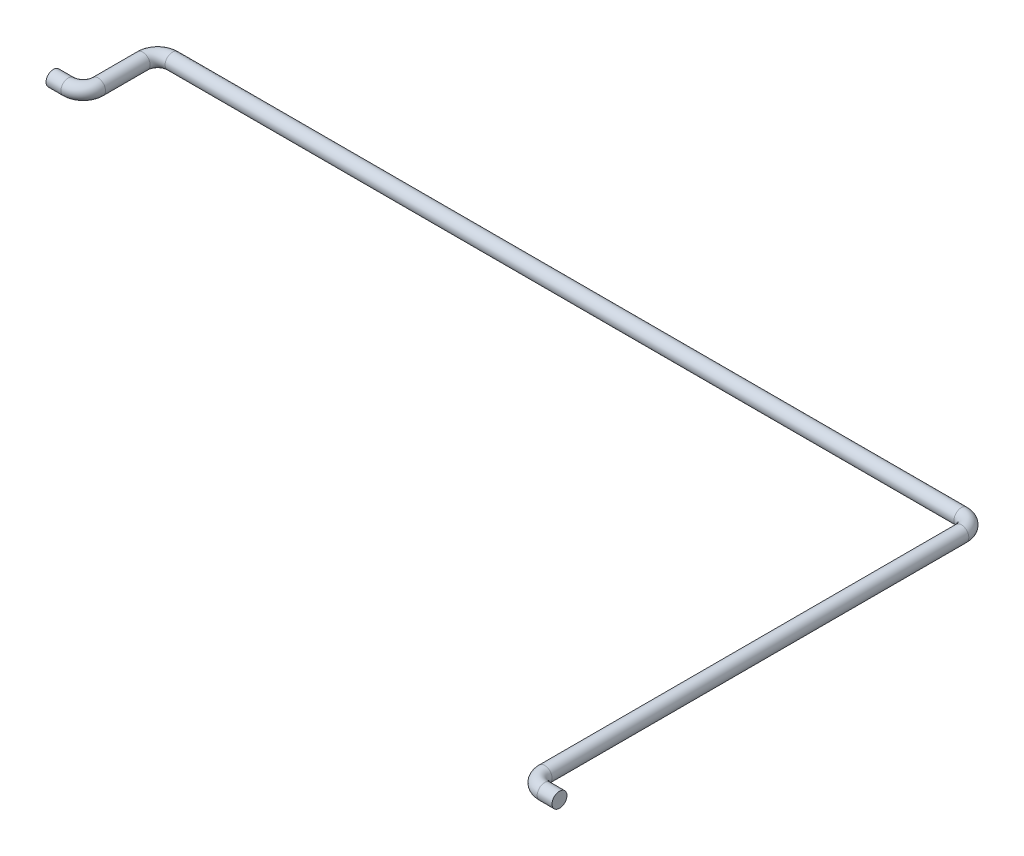
SolidWorks part; units mm, degrees
material "Stainless Steel (ferritic)"
ref_plane "Front" through (0, 0, 0) normal (0, 0, 1) x (1, 0, 0)
ref_plane "Top" through (0, 0, 0) normal (0, 1, 0) x (1, 0, 0)
ref_plane "Right" through (0, 0, 0) normal (1, 0, 0) x (0, 0, -1)
sketch "Sketch1" plane through (0, 0, 0) normal (0, 1, 0) x (1, 0, 0)
  line L0 (2, 1) -> (2, 4)
  line L1 (3, 5) -> (56, 5)
  line L2 (57, 4) -> (57, -24)
  line L3 (58, -25) -> (59, -25)
  line L4 (1, 0) -> (0, 0)
  arc A0 (2, 4) -> (3, 5) centre (3, 4) cw
  arc A1 (56, 5) -> (57, 4) centre (56, 4) cw
  arc A2 (57, -24) -> (58, -25) centre (58, -24) ccw
  arc A3 (2, 1) -> (1, 0) centre (1, 1) cw
  dimension "D2" = 1
  dimension "D1" = 55
  dimension "D3" = 3
  dimension "D4" = 1
  dimension "D5" = 28
sketch "Sketch2" plane through (0, 0, 0) normal (1, 0, 0) x (0, 0, -1)
  circle A0 centre (0, 0) radius 0.5
  dimension "D1" = 1
sweep "Sweep1" add profiles "Sketch2" path "Sketch1"
